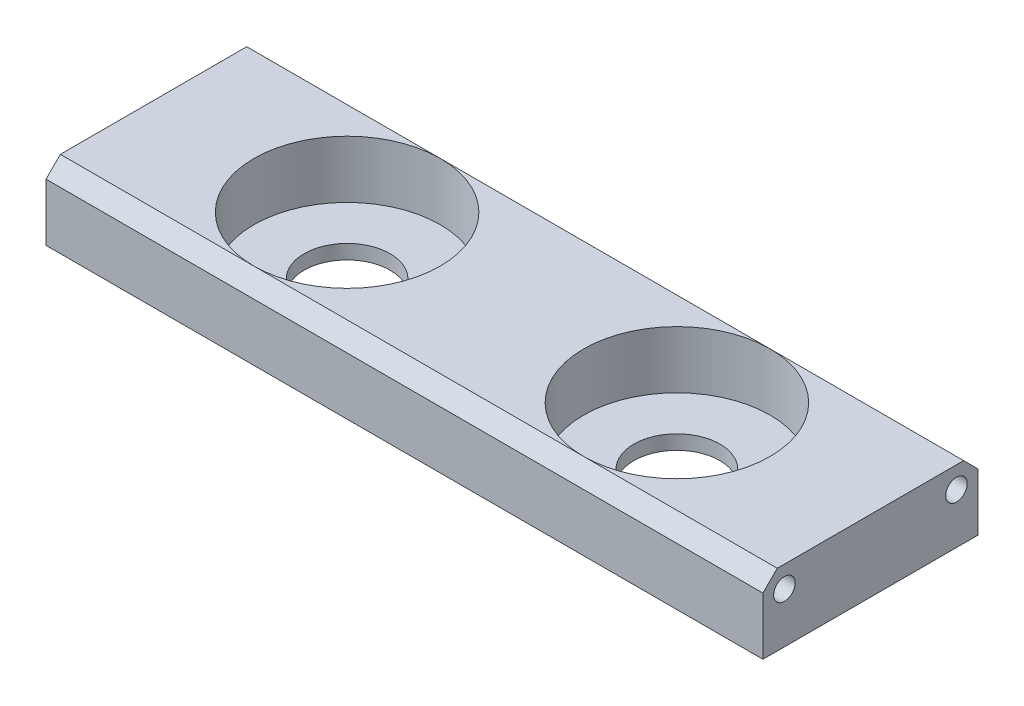
SolidWorks part; units mm, degrees
ref_plane "Front Plane" through (0, 0, 0) normal (0, 0, 1) x (1, 0, 0)
ref_plane "Top Plane" through (0, 0, 0) normal (0, 1, 0) x (1, 0, 0)
ref_plane "Right Plane" through (0, 0, 0) normal (1, 0, 0) x (0, 0, -1)
sketch "Sketch1" plane through (0, 0, 0) normal (0, 1, 0) x (1, 0, 0)
  line L1 (0, 0) -> (100, 0)
  line L2 (0, 0) -> (0, 30)
  line L3 (0, 30) -> (100, 30)
  line L4 (100, 0) -> (100, 30)
  dimension "D1" = 30
  dimension "D2" = 100
extrude "Boss-Extrude1" add sketch "Sketch1" along normal blind 6
sketch "Sketch2" plane through (0, 6, 0) normal (0, 1, 0) x (1, 0, 0)
  line L0 (0, 15) -> (100, 15) construction
  line L1 (0, 30) -> (0, 0) construction
  line L2 (100, 0) -> (100, 30) construction
  circle A0 centre (27, 15) radius 6
  circle A1 centre (73, 15) radius 6
  dimension "D1" = 12
  dimension "D2" = 12
  dimension "D3" = 27
  dimension "D4" = 27
  dimension "D5" = 46
extrude "Cut-Extrude1" cut sketch "Sketch2" against normal through all
chamfer "Chamfer1" distance 2 angle 45 2 edges at (50, 6, -30) (50, 6, 0)
sketch "Sketch3" plane through (100, 0, 0) normal (1, 0, 0) x (0, 0, -1)
  line L0 (0, 3) -> (30, 3) construction
  line L1 (0, 4) -> (0, 0) construction
  line L2 (30, 4) -> (30, 0) construction
  line L3 (0, 0) -> (30, 0) construction
  circle A0 centre (3, 3) radius 1.5
  circle A1 centre (27, 3) radius 1.5
  dimension "D2" = 3
  dimension "D3" = 3
  dimension "D1" = 3
  dimension "D4" = 3
  dimension "D5" = 3
extrude "Cut-Extrude2" cut sketch "Sketch3" against normal blind 7
sketch "Sketch4" plane through (0, 0, 0) normal (-1, 0, 0) x (0, 0, 1)
  line L0 (-30, 3) -> (0, 3) construction
  line L1 (-30, 4) -> (-30, 0) construction
  line L2 (0, 4) -> (0, 0) construction
  line L3 (-30, 0) -> (0, 0) construction
  circle A0 centre (-27, 3) radius 1.5
  circle A1 centre (-3, 3) radius 1.5
  dimension "D2" = 3
  dimension "D1" = 3
  dimension "D3" = 3
extrude "Cut-Extrude3" cut sketch "Sketch4" against normal blind 7
sketch "Sketch5" plane through (0, 0, 0) normal (0, -1, 0) x (1, 0, 0)
  line L1 (0, 0) -> (100, 0)
  line L2 (0, 0) -> (0, -30)
  line L3 (0, -30) -> (100, -30)
  line L4 (100, 0) -> (100, -30)
  circle A0 centre (27, -15) radius 6
  circle A1 centre (73, -15) radius 6
extrude "Boss-Extrude2" add sketch "Sketch5" along normal blind 4
sketch "Sketch6" plane through (0, 6, 0) normal (0, 1, 0) x (1, 0, 0)
  circle A0 centre (27, 15) radius 13
  circle A1 centre (73, 15) radius 13
  dimension "D1" = 26
  dimension "D2" = 26
extrude "Cut-Extrude4" cut sketch "Sketch6" against normal blind 8
